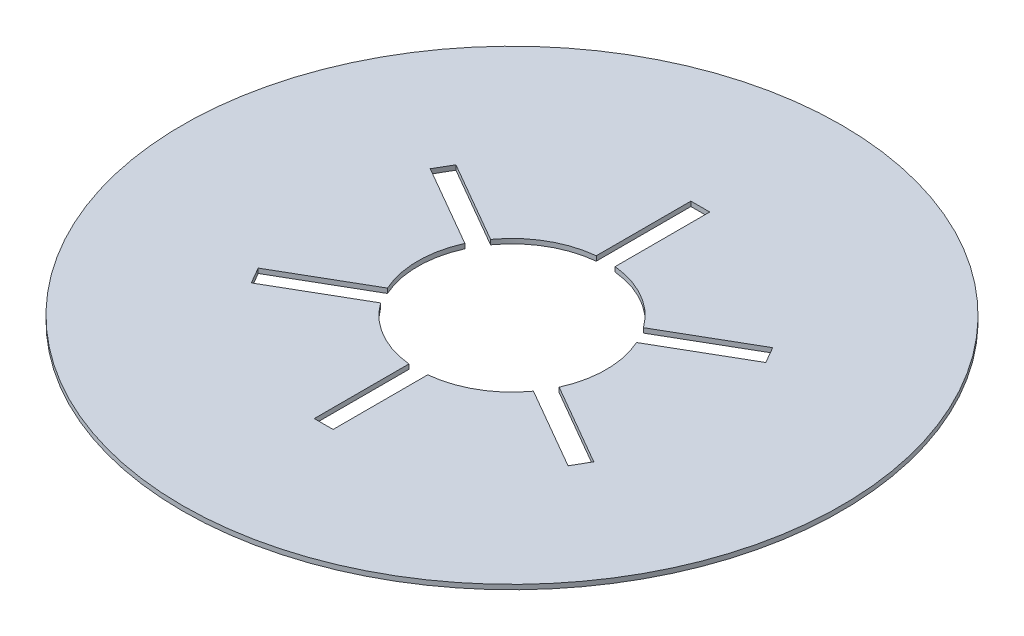
SolidWorks part; units mm, degrees
ref_plane "Ön Düzlem" through (0, 0, 0) normal (0, 0, 1) x (1, 0, 0)
ref_plane "Üst Düzlem" through (0, 0, 0) normal (0, 1, 0) x (1, 0, 0)
ref_plane "Sağ Düzlem" through (0, 0, 0) normal (1, 0, 0) x (0, 0, -1)
sketch "Çizim1" plane through (0, 0, 0) normal (0, 1, 0) x (1, 0, 0)
  line L0 (81.1684, 58.4096) -> (168.2051, 108.6603)
  line L1 (-150, 55.7008) -> (-96.8246, 25)
  line L2 (-10, 99.4987) -> (-10, 200)
  line L3 (-10, 200) -> (10, 200)
  line L4 (10, 99.4987) -> (10, 200)
  line L5 (91.1684, 41.0891) -> (178.2051, 91.3397)
  line L6 (168.2051, 108.6603) -> (178.2051, 91.3397)
  line L7 (-150, 55.7008) -> (-150, -55.7008)
  line L8 (91.1684, -41.0891) -> (178.2051, -91.3397)
  line L9 (81.1684, -58.4096) -> (168.2051, -108.6603)
  line L10 (178.2051, -91.3397) -> (168.2051, -108.6603)
  line L11 (-150, -55.7008) -> (-96.8246, -25)
  line L12 (10, -99.4987) -> (10, -200)
  line L13 (-10, -99.4987) -> (-10, -200)
  line L14 (10, -200) -> (-10, -200)
  line L15 (-26.7617, 157.7542) -> (-26.7617, 96.3525)
  line L16 (-81.1684, -58.4096) -> (-168.2051, -108.6603)
  line L17 (-91.1684, -41.0891) -> (-178.2051, -91.3397)
  line L18 (-168.2051, -108.6603) -> (-178.2051, -91.3397)
  line L19 (-26.7617, 157.7542) -> (-123.2383, 102.0534)
  line L20 (-91.1684, 41.0891) -> (-178.2051, 91.3397)
  line L21 (-81.1684, 58.4096) -> (-168.2051, 108.6603)
  line L22 (-178.2051, 91.3397) -> (-168.2051, 108.6603)
  line L23 (-123.2383, 102.0534) -> (-70.0629, 71.3525)
  line L25 (123.2383, 102.0534) -> (70.0629, 71.3525)
  line L26 (123.2383, 102.0534) -> (26.7617, 157.7542)
  line L27 (26.7617, 157.7542) -> (26.7617, 96.3525)
  line L28 (150, -55.7008) -> (96.8246, -25)
  line L29 (150, -55.7008) -> (150, 55.7008)
  line L30 (150, 55.7008) -> (96.8246, 25)
  line L31 (26.7617, -157.7542) -> (26.7617, -96.3525)
  line L32 (26.7617, -157.7542) -> (123.2383, -102.0534)
  line L33 (123.2383, -102.0534) -> (70.0629, -71.3525)
  line L34 (-123.2383, -102.0534) -> (-70.0629, -71.3525)
  line L35 (-123.2383, -102.0534) -> (-26.7617, -157.7542)
  line L36 (-26.7617, -157.7542) -> (-26.7617, -96.3525)
  circle A0 centre (0, 0) radius 350
  arc A1 (-91.1684, 41.0891) -> (-91.1684, -41.0891) centre (0, 0) ccw
  arc A2 (-10, 99.4987) -> (-81.1684, 58.4096) centre (0, 0) ccw
  arc A3 (81.1684, 58.4096) -> (10, 99.4987) centre (0, 0) ccw
  arc A4 (91.1684, -41.0891) -> (91.1684, 41.0891) centre (0, 0) ccw
  arc A5 (-81.1684, -58.4096) -> (-10, -99.4987) centre (0, 0) ccw
  arc A6 (10, -99.4987) -> (81.1684, -58.4096) centre (0, 0) ccw
  point P31 (0, 0)
  point P57 (0, 0)
  dimension "D1" = 700
  dimension "D2" = 200
  dimension "D3" = 20
  dimension "D4" = 10
  dimension "D5" = 200
  dimension "D6" = 41.0891
  dimension "D8" = 50
  dimension "D9" = 150
  dimension "D10" = 6
  dimension "D7" = 6
extrude "Yükseklik-Ekstrüzyon1" add sketch "Çizim1" along normal blind 5 contours A0 A6 L12 L14 L13 A5 L36 L35 L34 L16 L18 L17 A1 L11 L7 L1 L20 L22 L21 A2 L23 L19 L15 L2 L3 L4 A3 L27 L26 L25 L0 L6 L5 A4 L30 L29 L28 L8 L10 L9 L33 L32 L31 | A5 L34 L35 L36 | A1 L1 L7 L11 | A2 L15 L19 L23 | A3 L25 L26 L27 | A4 L28 L29 L30 | A6 L31 L32 L33
